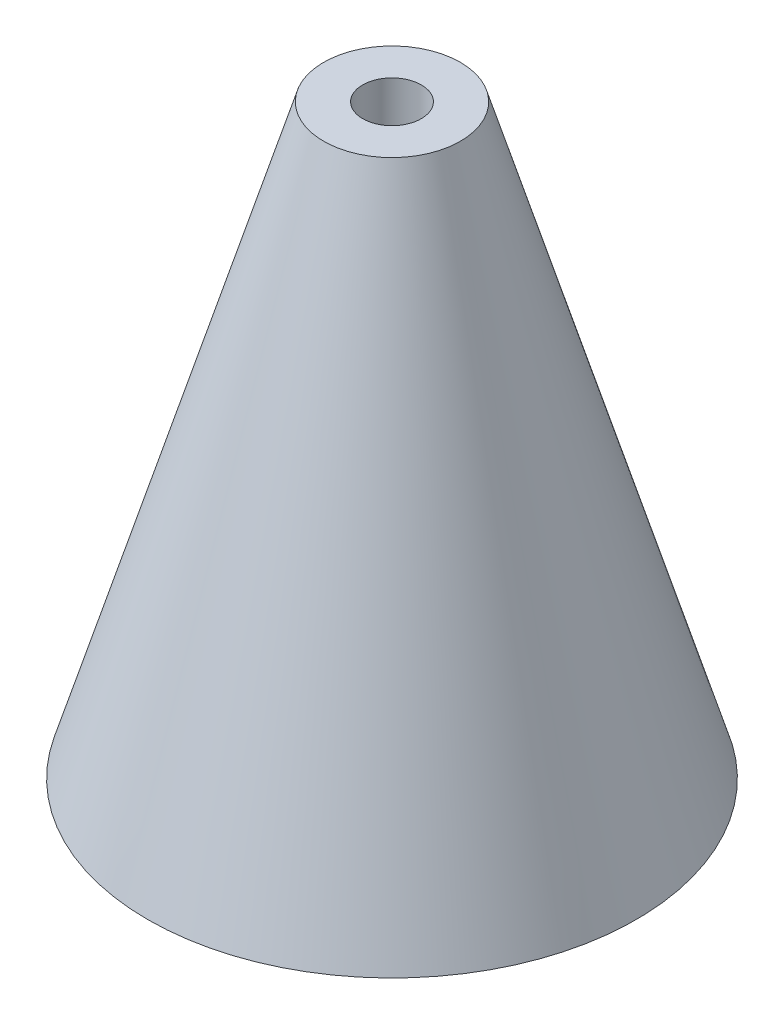
SolidWorks part; units mm, degrees
ref_plane "Спереди" through (0, 0, 0) normal (0, 0, 1) x (1, 0, 0)
ref_plane "Сверху" through (0, 0, 0) normal (0, 1, 0) x (1, 0, 0)
ref_plane "Справа" through (0, 0, 0) normal (1, 0, 0) x (0, 0, -1)
sketch "Эскиз1" plane through (0, 0, 0) normal (0, 0, 1) x (1, 0, 0)
  line L0 (0, 0) -> (0, 60) construction
  line L1 (-25, 0) -> (25, 0) construction
  line L2 (3, 60) -> (3, 0)
  line L3 (7, 60) -> (25, 0)
  line L4 (3, 60) -> (7, 60)
  line L5 (3, 0) -> (25, 0)
  point P6 (0, 0)
  dimension "D1" = 60
  dimension "D2" = 50
  dimension "D3" = 6
  dimension "D4" = 4
revolve "Повернуть1" add sketch "Эскиз1" angle 360 about L0
